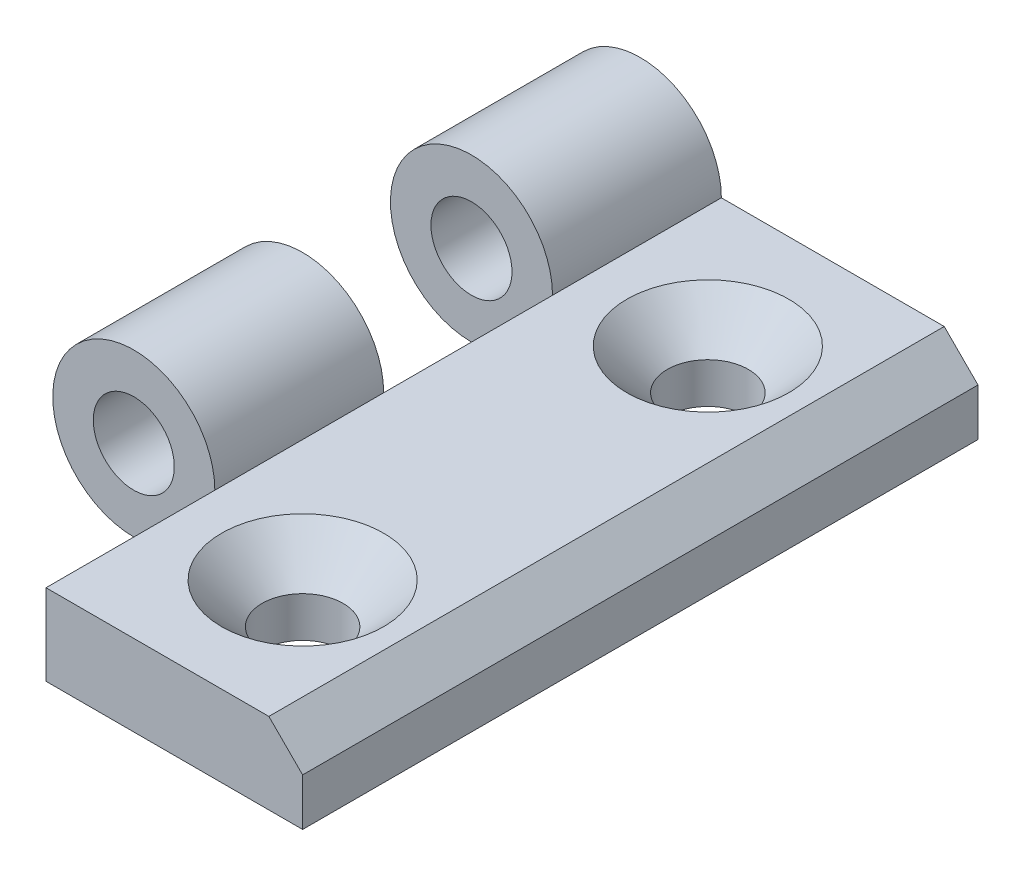
SolidWorks part; units mm, degrees
ref_plane "前视基准面" through (0, 0, 0) normal (0, 0, 1) x (1, 0, 0)
ref_plane "上视基准面" through (0, 0, 0) normal (0, 1, 0) x (1, 0, 0)
ref_plane "右视基准面" through (0, 0, 0) normal (1, 0, 0) x (0, 0, -1)
sketch "草图1" plane through (0, 0, 0) normal (0, 0, 1) x (1, 0, 0)
  circle A0 centre (-36.9997, 47.3326) radius 6
extrude "凸台-拉伸1" add sketch "草图1" along normal blind 50
sketch "草图2" plane through (0, 0, 50) normal (0, 0, 1) x (1, 0, 0)
  line L0 (-36.9997, 47.3326) -> (-36.9997, 41.3326)
  line L1 (-36.9997, 41.3326) -> (-11.9997, 41.3326)
  line L2 (-36.9997, 47.3326) -> (-11.9997, 47.3326)
  line L3 (-11.9997, 47.3326) -> (-11.9997, 41.3326)
  circle A0 centre (-36.9997, 47.3326) radius 6 construction
  point P6 (-36.9997, 47.3326)
extrude "凸台-拉伸2" add sketch "草图2" against normal blind 50
sketch "草图5" plane through (0, 0, 50) normal (0, 0, 1) x (1, 0, 0)
  circle A0 centre (-36.9997, 47.3326) radius 3
  point P6 (-36.9997, 47.3326)
extrude "切除-拉伸1" cut sketch "草图5" against normal blind 50
hole_wizard "打孔尺寸(%根据)内六角花形半沉头螺钉的类型1" positions "草图7" profile "草图6" countersink size "M6" standard "GB" end condition through all
sketch "草图7" plane through (0, 47.3326, 0) normal (0, 1, 0) x (1, 0, 0)
  line L0 (-21.9997, -10) -> (-21.9997, -40)
  line L2 (-11.9997, -40) -> (-21.9997, -40)
  line L3 (-11.9997, 0) -> (-11.9997, -50) construction
  line L7 (-21.9997, -40) -> (-21.9997, -50)
  line L8 (-11.9997, -50) -> (-30.9997, -50) construction
  point P0 (-21.9997, -40)
  point P2 (-21.9997, -10)
sketch "草图6" plane through (-21.9997, 47.3326, 40) normal (1, 0, 0) x (0, 0, 1)
  line L0 (0, 0) -> (0, 6)
  line L1 (0, 6) -> (3, 6)
  line L2 (3, 6) -> (3, 3)
  line L3 (3, 3) -> (6, 0)
  line L5 (6, 0) -> (0, 0)
  line L6 (-3, 3) -> (-6, 0) construction
  line L11 (0, -6.35) -> (0, 107.95) construction
  dimension "通孔孔直径" = 6
  dimension "通孔孔深度" = 6
  dimension "近端锥形沉头孔直径" = 12
  dimension "近端锥形沉头孔角度" = 90
sketch "草图9" plane through (0, 0, 50) normal (0, 0, 1) x (1, 0, 0)
  line L1 (-30.9997, 47.3326) -> (-30.9997, 35.8181)
  line L2 (-30.9997, 35.8181) -> (-46.0001, 35.8181)
  line L3 (-46.0001, 35.8181) -> (-46.0001, 53.9091)
  line L4 (-46.0001, 53.9091) -> (-30.9997, 53.9091)
  line L5 (-30.9997, 53.9091) -> (-30.9997, 47.3326)
extrude "切除-拉伸2" cut sketch "草图9" against normal blind 12.5
pattern_linear "阵列(线性)2" count 2 spacing 25 along (0, 0, -1) of "切除-拉伸2"
chamfer "倒角1" distance 2.5 angle 45 1 edges at (-11.9997, 47.3326, 25)
